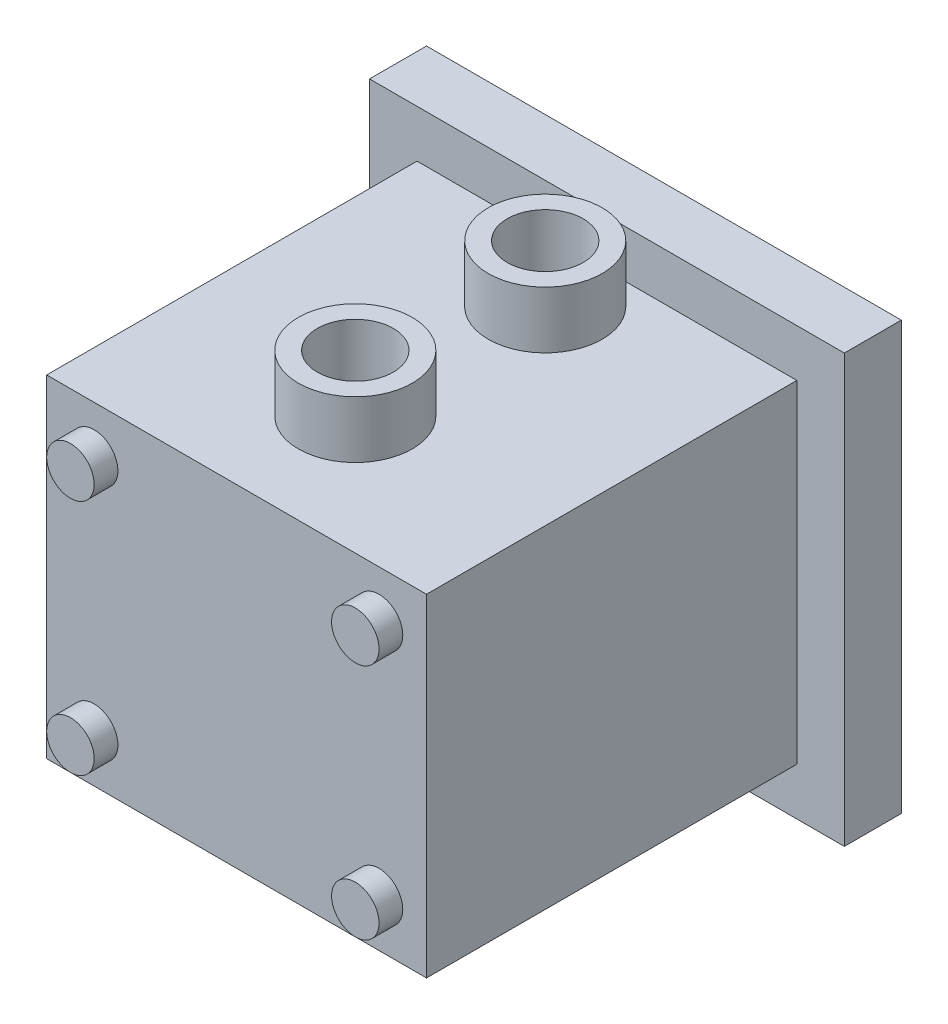
SolidWorks part; units mm, degrees
other "Cast_iron_cover_GRADE_UNSPECIFIED"
other "Aluminium_housing_GRADE_UNSPECIFIED"
ref_plane "Front Plane" through (0, 0, 0) normal (0, 0, 1) x (1, 0, 0)
ref_plane "Top Plane" through (0, 0, 0) normal (0, 1, 0) x (1, 0, 0)
ref_plane "Right Plane" through (0, 0, 0) normal (1, 0, 0) x (0, 0, -1)
sketch "Sketch1" plane through (0, 0, 0) normal (0, 0, 1) x (1, 0, 0)
  line L1 (-40, -35) -> (40, -35)
  line L2 (-40, -35) -> (-40, 35)
  line L3 (-40, 35) -> (40, 35)
  line L4 (40, -35) -> (40, 35)
extrude "Housing_80x70x78_ASSUMED" add sketch "Sketch1" along normal blind 78 from offset 12 separate body
sketch "Sketch2" plane through (0, 0, 0) normal (0, 0, 1) x (1, 0, 0)
  line L1 (-50, -45) -> (50, -45)
  line L2 (-50, -45) -> (-50, 45)
  line L3 (-50, 45) -> (50, 45)
  line L4 (50, -45) -> (50, 45)
extrude "Flange_100x90_ASSUMED" add sketch "Sketch2" along normal blind 12 from offset 0 separate body
sketch "Sketch3" plane through (0, 0, 0) normal (0, 0, 1) x (1, 0, 0)
  circle A0 centre (0, 0) radius 9.525
extrude "Shaft_D19p05_listing_length_ASSUMED" add sketch "Sketch3" against normal blind 30 from offset 0 separate body
sketch "Sketch4" plane through (0, 0, 0) normal (0, 0, 1) x (1, 0, 0)
  circle A0 centre (-30, -25) radius 5
extrude "Fastener_envelope_ASSUMED" add sketch "Sketch4" along normal blind 5 from offset 90 separate body
sketch "Sketch5" plane through (0, 0, 0) normal (0, 0, 1) x (1, 0, 0)
  circle A0 centre (-30, 25) radius 5
extrude "Boss-Extrude5" add sketch "Sketch5" along normal blind 5 from offset 90 separate body
sketch "Sketch6" plane through (0, 0, 0) normal (0, 0, 1) x (1, 0, 0)
  circle A0 centre (30, -25) radius 5
extrude "Boss-Extrude6" add sketch "Sketch6" along normal blind 5 from offset 90 separate body
sketch "Sketch7" plane through (0, 0, 0) normal (0, 0, 1) x (1, 0, 0)
  circle A0 centre (30, 25) radius 5
extrude "Boss-Extrude7" add sketch "Sketch7" along normal blind 5 from offset 90 separate body
sketch "Sketch8" plane through (0, 0, 0) normal (0, 1, 0) x (1, 0, 0)
  circle A0 centre (0, -25) radius 12
  circle A1 centre (0, -25) radius 8
extrude "Inlet_3_8NPT_port_location_ASSUMED" add sketch "Sketch8" along normal blind 12 from offset 35 separate body
sketch "Sketch9" plane through (0, 0, 0) normal (0, 1, 0) x (1, 0, 0)
  circle A0 centre (0, -65) radius 12
  circle A1 centre (0, -65) radius 8
extrude "Outlet_3_8NPT_port_location_ASSUMED" add sketch "Sketch9" along normal blind 12 from offset 35 separate body
